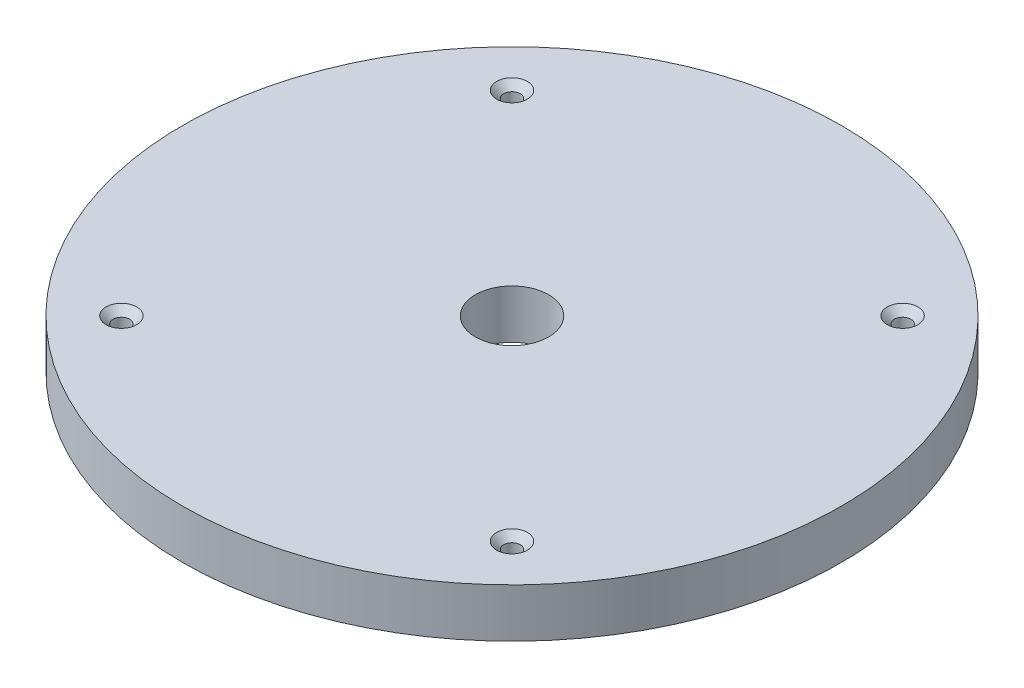
SolidWorks part; units mm, degrees
material "1060 Alloy"
ref_plane "Front Plane" through (0, 0, 0) normal (0, 0, 1) x (1, 0, 0)
ref_plane "Top Plane" through (0, 0, 0) normal (0, 1, 0) x (1, 0, 0)
ref_plane "Right Plane" through (0, 0, 0) normal (1, 0, 0) x (0, 0, -1)
sketch "Sketch1" plane through (0, 0, 0) normal (0, 1, 0) x (1, 0, 0)
  circle A0 centre (0, 0) radius 67.5
  dimension "D1" = 135
extrude "Boss-Extrude1" add sketch "Sketch1" along normal blind 10
hole_wizard "CSK for M3 Countersunk Flat Head Screw1" positions "Sketch3" profile "Sketch4" countersink size "M3" standard "DIN" end condition through all
sketch "Sketch3" plane through (0, 10, 0) normal (0, 1, 0) x (1, 0, 0)
  point P0 (-40, 40)
  point P8 (40, 40)
  point P9 (40, -40)
  point P10 (-40, -40)
  dimension "D3" = 80
  dimension "D4" = 80
  dimension "D5" = 40
  dimension "D6" = 40
  dimension "D1" = 2
  dimension "D2" = 2
sketch "Sketch4" plane through (-40, 10, -40) normal (1, 0, 0) x (0, 0, 1)
  line L0 (0, 0) -> (0, 10)
  line L1 (0, 10) -> (1.7, 10)
  line L2 (1.7, 10) -> (1.7, 1.45)
  line L3 (1.7, 1.45) -> (3.15, 0)
  line L5 (3.15, 0) -> (0, 0)
  line L6 (-1.7, 1.45) -> (-3.15, 0) construction
  line L11 (0, -6.35) -> (0, 107.95) construction
  dimension "Thru Hole Dia." = 3.4
  dimension "Thru Hole Depth" = 10
  dimension "Near C'Sink Dia." = 6.3
  dimension "Near C'Sink Angle" = 90
sketch "Sketch5" plane through (0, 10, 0) normal (0, 1, 0) x (1, 0, 0)
  circle A0 centre (0, 0) radius 7.5
  dimension "D1" = 15
extrude "Cut-Extrude1" cut sketch "Sketch5" against normal through all
equation "\"Plate Diameter\"= 135mm"
equation "\"Plate Thickness\"= 10mm"
equation "\"D1@Sketch1\"=\"Plate Diameter\""
equation "\"D1@Boss-Extrude1\"=\"Plate Thickness\""
